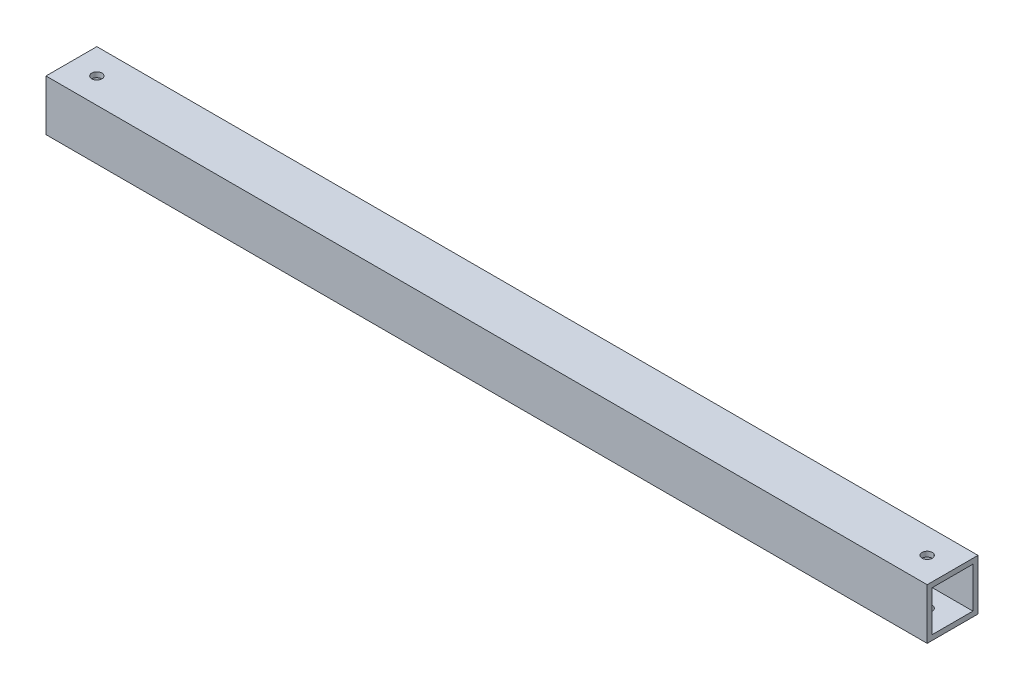
SolidWorks part; units mm, degrees
ref_plane "正面" through (0, 0, 0) normal (0, 0, 1) x (1, 0, 0)
ref_plane "平面" through (0, 0, 0) normal (0, 1, 0) x (1, 0, 0)
ref_plane "右側面" through (0, 0, 0) normal (1, 0, 0) x (0, 0, -1)
sketch "ｽｹｯﾁ2" plane through (0, 0, 0) normal (0, 0, 1) x (1, 0, 0)
  line L1 (0, 0) -> (260, 0)
  line L2 (0, 0) -> (0, 15)
  line L3 (0, 15) -> (260, 15)
  line L4 (260, 0) -> (260, 15)
  dimension "D1" = 260
  dimension "D2" = 15
extrude "ﾎﾞｽ - 押し出し1" add sketch "ｽｹｯﾁ2" along normal blind 15
sketch "ｽｹｯﾁ3" plane through (0, 15, 0) normal (0, 1, 0) x (1, 0, 0)
  line L0 (260, -7.5) -> (0, -7.5) construction
  line L1 (260, -15) -> (260, 0) construction
  line L2 (0, -15) -> (0, 0) construction
  circle A0 centre (7.5, -7.5) radius 1.5
  circle A1 centre (252.5, -7.5) radius 1.5
  dimension "D1" = 3
  dimension "D2" = 7.5
  dimension "D3" = 7.5
extrude "ｶｯﾄ - 押し出し1" cut sketch "ｽｹｯﾁ3" against normal through all
sketch "ｽｹｯﾁ4" plane through (260, 0, 0) normal (1, 0, 0) x (0, 0, -1)
  line L8 (-1.5, 1.5) -> (-1.5, 13.5)
  line L9 (-1.5, 13.5) -> (-13.5, 13.5)
  line L10 (-13.5, 13.5) -> (-13.5, 1.5)
  line L11 (-13.5, 1.5) -> (-1.5, 1.5)
  line L12 (-1.5, 1.5) -> (-1.5, 13.5)
  line L13 (-1.5, 13.5) -> (-13.5, 13.5)
  line L14 (-13.5, 13.5) -> (-13.5, 1.5)
  line L15 (-13.5, 1.5) -> (-1.5, 1.5)
  dimension "D1" = 1.5
extrude "ｶｯﾄ - 押し出し2" cut sketch "ｽｹｯﾁ4" against normal through all
